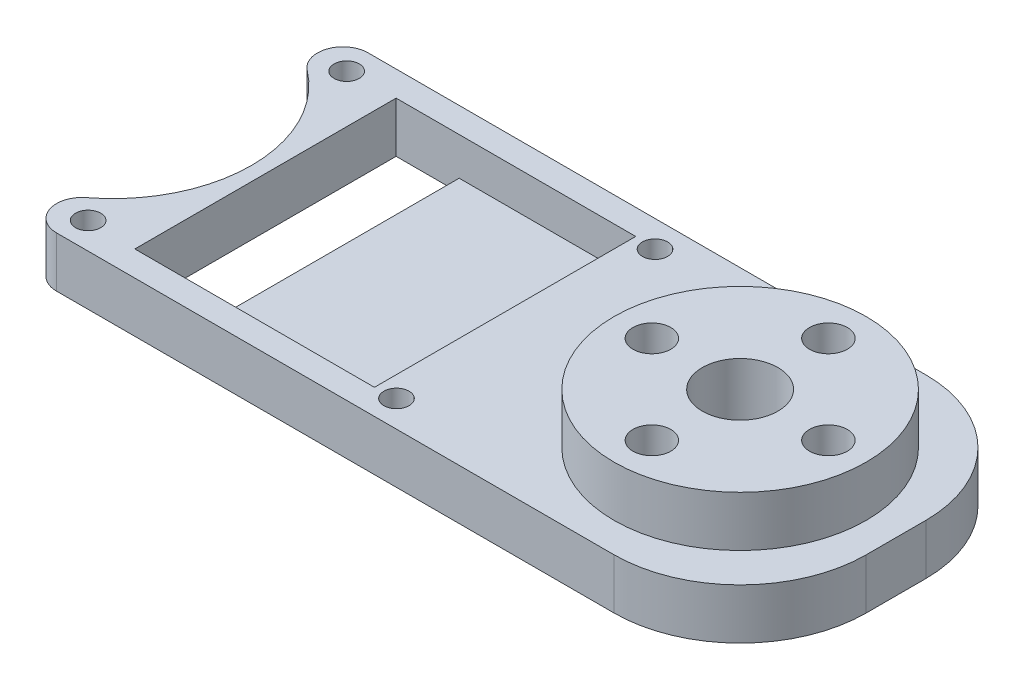
SolidWorks part; units mm, degrees
ref_plane "前视基准面" through (0, 0, 0) normal (0, 0, 1) x (1, 0, 0)
ref_plane "上视基准面" through (0, 0, 0) normal (0, 1, 0) x (1, 0, 0)
ref_plane "右视基准面" through (0, 0, 0) normal (1, 0, 0) x (0, 0, -1)
other "Configuration Table"
ref_plane "基准面1" through (0, 0, 0) normal (0, 1, 0) x (1, 0, 0)
sketch "草图1" plane through (0, 0, 0) normal (0, 1, 0) x (1, 0, 0)
  line L0 (6.61, -12.36) -> (9.61, -12.36)
  line L1 (-32.61, -12.36) -> (6.61, -12.36)
  line L2 (-35.61, -9.36) -> (-35.61, 9.36)
  line L3 (-32.61, 12.36) -> (6.61, 12.36)
  line L4 (9.61, -9.36) -> (9.61, 9.36)
  line L5 (9.61, -12.36) -> (9.61, -9.36)
  line L6 (6.61, 12.36) -> (9.61, 12.36)
  line L7 (9.61, 12.36) -> (9.61, 9.36)
  arc A1 (-32.61, 12.36) -> (-35.61, 9.36) centre (-32.61, 9.36) ccw
  arc A2 (-35.61, -9.36) -> (-32.61, -12.36) centre (-32.61, -9.36) ccw
extrude "凸台-拉伸1" add sketch "草图1" along normal blind 4
sketch "草图2" plane through (0, 0, 0) normal (0, 1, 0) x (1, 0, 0)
  circle A0 centre (7.25, -10.25) radius 1
  circle A1 centre (7.25, 10.25) radius 1
  circle A2 centre (-17.2, -10.25) radius 1
  circle A3 centre (-17.2, 10.25) radius 1
  dimension "D1" = 2
  dimension "D2" = 2
  dimension "D3" = 2
  dimension "D4" = 2
extrude "切除-拉伸1" cut sketch "草图2" against normal through all and the other way through all
sketch "草图3" plane through (0, 4, 0) normal (0, 1, 0) x (1, 0, 0)
  line L0 (9.61, 12.36) -> (-32.61, 12.36) construction
  line L1 (-8.39, -10.36) -> (5.61, -10.36)
  line L2 (-8.39, -10.36) -> (-8.39, 10.36)
  line L3 (-8.39, 10.36) -> (5.61, 10.36)
  line L4 (5.61, -10.36) -> (5.61, 10.36)
  line L9 (9.61, -12.36) -> (9.61, 12.36) construction
  line L10 (-32.61, -12.36) -> (9.61, -12.36) construction
  dimension "D1" = 2
  dimension "D2" = 4
  dimension "D3" = 2
  dimension "D4" = 14
extrude "切除-拉伸3" cut sketch "草图3" against normal blind 3
sketch "草图5" plane through (0, 4, 0) normal (0, 1, 0) x (1, 0, 0)
  line L0 (9.61, 12.36) -> (-32.61, 12.36) construction
  line L1 (-13.39, 10.36) -> (-8.39, 10.36)
  line L2 (-13.39, 10.36) -> (-13.39, -10.36)
  line L3 (-13.39, -10.36) -> (-8.39, -10.36)
  line L4 (-8.39, 10.36) -> (-8.39, -10.36)
  line L5 (-8.39, 10.36) -> (-8.39, -10.36) construction
  line L6 (-32.61, -12.36) -> (9.61, -12.36) construction
  dimension "D1" = 2
  dimension "D2" = 0
  dimension "D3" = 2
  dimension "D4" = 5
extrude "切除-拉伸4" cut sketch "草图5" against normal blind 4
sketch "草图6" plane through (0, 4, 0) normal (0, 1, 0) x (1, 0, 0)
  line L0 (9.61, -12.36) -> (9.61, 12.36) construction
  circle A0 centre (-25.5, 0) radius 11
  dimension "D2" = 22
  dimension "D1" = 35.11
sketch "草图13" plane through (9.61, 0, 0) normal (1, 0, 0) x (0, 0, -1)
  line L4 (-12.36, 0) -> (12.36, 0)
  line L5 (12.36, 0) -> (12.36, 4)
  line L6 (12.36, 4) -> (-12.36, 4)
  line L7 (-12.36, 4) -> (-12.36, 0)
  line L8 (-12.36, 0) -> (12.36, 0)
  line L9 (12.36, 0) -> (12.36, 4)
  line L10 (12.36, 4) -> (-12.36, 4)
  line L11 (-12.36, 4) -> (-12.36, 0)
  dimension "D1" = 0
extrude "凸台-拉伸5" add sketch "草图13" along normal blind 27
sketch "草图15" plane through (0, 4, 0) normal (0, 1, 0) x (1, 0, 0)
  line L0 (36.61, 12.36) -> (-32.61, 12.36) construction
  line L1 (36.61, 12.36) -> (36.61, -12.36) construction
  circle A0 centre (24.25, 0) radius 10
  dimension "D1" = 20
  dimension "D2" = 12.36
  dimension "D3" = 12.36
extrude "凸台-拉伸6" add sketch "草图15" along normal blind 4
sketch "草图14" plane through (0, 4, 0) normal (0, 1, 0) x (1, 0, 0)
  line L0 (36.61, 12.36) -> (36.61, -12.36) construction
  line L1 (36.61, 12.36) -> (-32.61, 12.36) construction
  circle A0 centre (24.25, 0) radius 10
  circle A1 centre (24.25, -7) radius 1.5
  circle A2 centre (31.25, 0) radius 1.5
  circle A3 centre (24.25, 7) radius 1.5
  circle A4 centre (17.25, 0) radius 1.5
  circle A5 centre (24.25, 0) radius 4.5
  point P4 (36.61, 0)
  dimension "D1" = 20
  dimension "D2" = 12.36
  dimension "D3" = 12.36
  dimension "D4" = 9
  dimension "D5" = 3
  dimension "D6" = 3
  dimension "D7" = 3
  dimension "D8" = 3
  dimension "D9" = 14
  dimension "D10" = 14
  dimension "D11" = 7
  dimension "D12" = 7
  dimension "D13" = 7
  dimension "D14" = 5.36
  dimension "D15" = 5.36
  dimension "D16" = 12.36
extrude "切除-拉伸7" cut sketch "草图14" along normal mid plane 8 contours A1 | A4 | A2 | A3
fillet "圆角1" radius 10 1 edges at (36.61, 2, -12.36)
fillet "圆角2" radius 10 1 edges at (36.61, 2, 12.36)
extrude "切除-拉伸9" cut sketch "草图6" against normal blind 4
sketch "草图17" plane through (-35.61, 0, 0) normal (-1, 0, 0) x (0, 0, 1)
  line L0 (-12.36, 4) -> (-12.36, 0) construction
  line L1 (-12.36, 4) -> (12.36, 4)
  line L2 (-12.36, 4) -> (-12.36, 0)
  line L3 (-12.36, 0) -> (12.36, 0)
  line L4 (12.36, 4) -> (12.36, 0)
  line L5 (-9.36, 4) -> (-4.3345, 4) construction
  line L6 (13.596, 0) -> (-13.596, 0) construction
  line L7 (12.36, 4) -> (12.36, 0) construction
  dimension "D1" = 0
  dimension "D2" = 0
  dimension "D3" = 0
extrude "切除-拉伸10" cut sketch "草图17" against normal blind 16
fillet "圆角3" radius 2 1 edges at (-19.61, 2, 12.36)
fillet "圆角4" radius 2 1 edges at (-19.61, 2, -12.36)
fillet "圆角5" radius 2 1 edges at (-19.61, 2, -9.2902)
fillet "圆角6" radius 2 1 edges at (-19.61, 2, 9.2902)
sketch "草图18" plane through (0, 8, 0) normal (0, 1, 0) x (1, 0, 0)
  circle A0 centre (24.25, 0) radius 3
  dimension "D1" = 6
extrude "切除-拉伸11" cut sketch "草图18" against normal blind 13
sketch "草图20" plane through (0, 0, 0) normal (0, -1, 0) x (1, 0, 0)
  circle A0 centre (24.25, 7) radius 3
  circle A1 centre (17.25, 0) radius 3
  circle A2 centre (24.25, -7) radius 3
  circle A3 centre (31.25, 0) radius 3
  dimension "D1" = 6
  dimension "D2" = 6
  dimension "D3" = 6
  dimension "D4" = 6
extrude "切除-拉伸12" cut sketch "草图20" against normal blind 3
